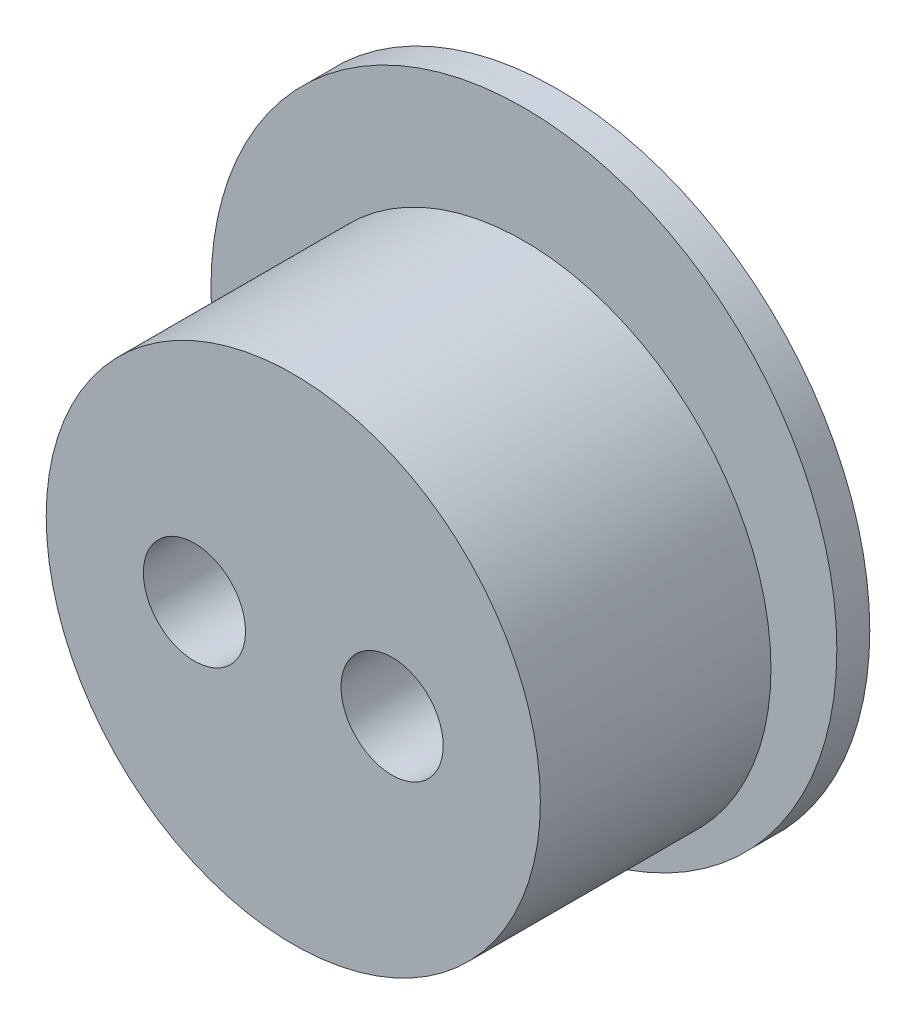
SolidWorks part; units mm, degrees
ref_plane "Front Plane" through (0, 0, 0) normal (0, 0, 1) x (1, 0, 0)
ref_plane "Top Plane" through (0, 0, 0) normal (0, 1, 0) x (1, 0, 0)
ref_plane "Right Plane" through (0, 0, 0) normal (1, 0, 0) x (0, 0, -1)
sketch "Sketch1" plane through (0, 0, 0) normal (0, 0, 1) x (1, 0, 0)
  circle A0 centre (0, 0) radius 9.5
  dimension "D1" = 19
extrude "Boss-Extrude1" add sketch "Sketch1" along normal blind 1
sketch "Sketch2" plane through (0, 0, 1) normal (0, 0, 1) x (1, 0, 0)
  line L0 (0, 9.8554) -> (0, -10.3269) construction
  circle A0 centre (0, -1.5) radius 7.5
  point P4 (0, 0)
  dimension "D1" = 15
  dimension "D2" = 1.5
extrude "Boss-Extrude2" add sketch "Sketch2" along normal blind 7
sketch "Sketch3" plane through (0, 0, 8) normal (0, 0, 1) x (1, 0, 0)
  line L0 (0, 9.772) -> (0, -10.4827) construction
  line L1 (-11.3711, -1.5) -> (10.0608, -1.5) construction
  circle A0 centre (3, -1.5) radius 1.55
  circle A1 centre (-3, -1.5) radius 1.55
  dimension "D2" = 3.1
  dimension "D1" = 1.5
  dimension "D3" = 3
extrude "Cut-Extrude1" cut sketch "Sketch3" against normal through all
